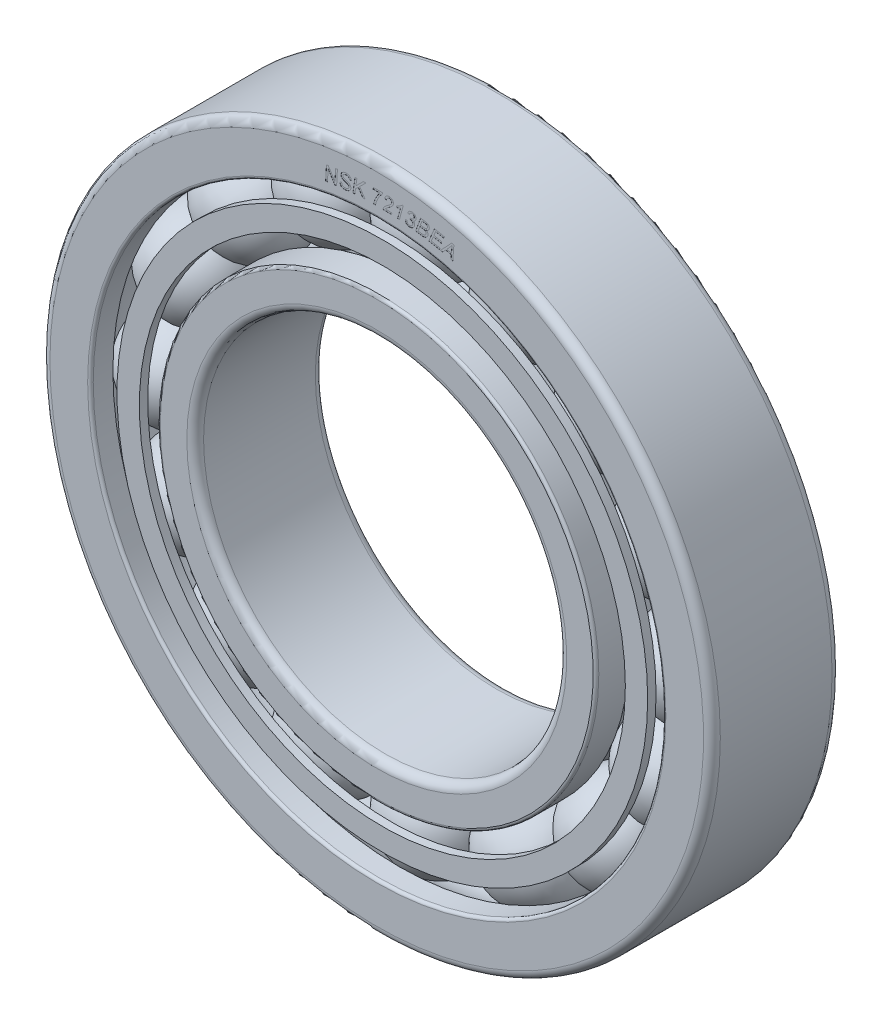
SolidWorks part; units mm, degrees
material "AISI 304"
ref_plane "Спереди" through (0, 0, 0) normal (0, 0, 1) x (1, 0, 0)
ref_plane "Сверху" through (0, 0, 0) normal (0, 1, 0) x (1, 0, 0)
ref_plane "Справа" through (0, 0, 0) normal (1, 0, 0) x (0, 0, -1)
sketch "Эскиз1" plane through (0, 0, 0) normal (1, 0, 0) x (0, 0, -1)
  line L0 (0, 0) -> (23, 0) construction
  line L1 (0, 0) -> (0, 60) construction
  line L2 (23, 0) -> (23, 32.5) construction
  line L3 (0, 60) -> (23, 60) construction
  line L4 (23, 60) -> (23, 32.5) construction
  line L5 (23, 32.5) -> (0, 32.5) construction
  line L6 (11.5, 60) -> (11.5, 32.5) construction
  line L7 (0, 39.25) -> (5.8431, 39.25)
  line L8 (23, 41.25) -> (18.9833, 41.25)
  line L9 (0, 39.25) -> (0, 32.5)
  line L10 (0, 32.5) -> (23, 32.5)
  line L11 (23, 32.5) -> (23, 41.25)
  line L12 (0, 51.25) -> (4.0167, 51.25)
  line L14 (0, 51.25) -> (0, 60)
  line L15 (0, 60) -> (23, 60)
  line L16 (23, 60) -> (23, 56)
  circle A0 centre (11.5, 46.25) radius 9 construction
  arc A1 (5.8431, 39.25) -> (18.9833, 41.25) centre (11.5, 46.25) ccw
  arc A2 (12.3631, 55.2085) -> (4.0167, 51.25) centre (11.5, 46.25) ccw
  arc A3 (23, 56) -> (12.3631, 55.2085) centre (15.3805, 86.528) cw
  point P13 (11.5, 37.25)
  point P15 (11.5, 55.25)
  point P21 (23, 56)
  dimension "D3" = 2
  dimension "15" = 18
  dimension "D1" = 23
  dimension "120" = 60
  dimension "D2" = 32.5
  dimension "D4" = 4
  dimension "D5" = 4
  dimension "D6" = 4
revolve "Повернуть1" add sketch "Эскиз1" angle 360 about L0
sketch "Эскиз2" plane through (0, 0, 0) normal (1, 0, 0) x (0, 0, -1)
  line L0 (11.5, 55.25) -> (11.5, 37.25)
  arc A0 (11.5, 37.25) -> (11.5, 55.25) centre (11.5, 46.25) cw
revolve "Повернуть2" add sketch "Эскиз2" angle 360 about L0
fillet "Скругление1" radius 1.5 2 edges at (60, 0, -23) (60, 0, 0)
fillet "Скругление2" radius 1.5 2 edges at (32.5, 0, 0) (32.5, 0, -23)
fillet "Скругление3" radius 0.5 2 edges at (51.25, 0, 0) (56, 0, -23)
fillet "Скругление4" radius 0.5 2 edges at (41.25, 0, -23) (39.25, 0, 0)
pattern_circular "Круговой массив1" count 16 over 360 about axis through (0, 0, 0) along (0, 0, 1) of bodies 105
sketch "Эскиз3" plane through (0, 0, 0) normal (0, 0, 1) x (1, 0, 0)
  line L0 (0, 53.25) -> (0, 0) construction
  line L1 (0, 0) -> (-13.7821, 51.4356) construction
  line L2 (0, 0) -> (13.7821, 51.4356) construction
  circle A2 centre (0, 0) radius 53.25
  arc A3 (13.7821, 51.4356) -> (-13.7821, 51.4356) centre (0, 0) ccw
  dimension "D2" = 15
  dimension "D1" = 2
sketch "Эскиз4" plane through (0, 0, 0) normal (0, 0, 1) x (1, 0, 0)
  text T0 "NSK 7213BEA" font "Arial" height in points 10
extrude "Вырез-Вытянуть1" cut sketch "Эскиз4" against normal blind 0.02
ref_plane "Плоскость1" through (0, 0, -1) normal (0, 0, 1) x (1, 0, 0)
sketch "Эскиз5" plane through (0, 0, -1) normal (0, 0, 1) x (1, 0, 0)
  circle A0 centre (0, 0) radius 47.5
  circle A1 centre (0, 0) radius 43.5
  dimension "D1" = 95
  dimension "D2" = 4
extrude "Бобышка-Вытянуть1" add sketch "Эскиз5" against normal blind 1.5 separate body
sketch "Эскиз6" plane through (0, 0, -23) normal (0, 0, -1) x (-1, 0, 0)
  circle A0 centre (0, 0) radius 50.5
  circle A1 centre (0, 0) radius 46.5
  dimension "D1" = 101
  dimension "D2" = 4
ref_plane "Плоскость2" through (0, 0, -22) normal (0, 0, -1) x (-1, 0, 0)
sketch "Эскиз7" plane through (0, 0, -22) normal (0, 0, -1) x (-1, 0, 0)
  circle A0 centre (0, 0) radius 46.5 construction
  circle A1 centre (0, 0) radius 50.5 construction
  circle A2 centre (0, 0) radius 46.5
  circle A3 centre (0, 0) radius 50.5
extrude "Бобышка-Вытянуть3" add sketch "Эскиз7" against normal blind 1.5 separate body
